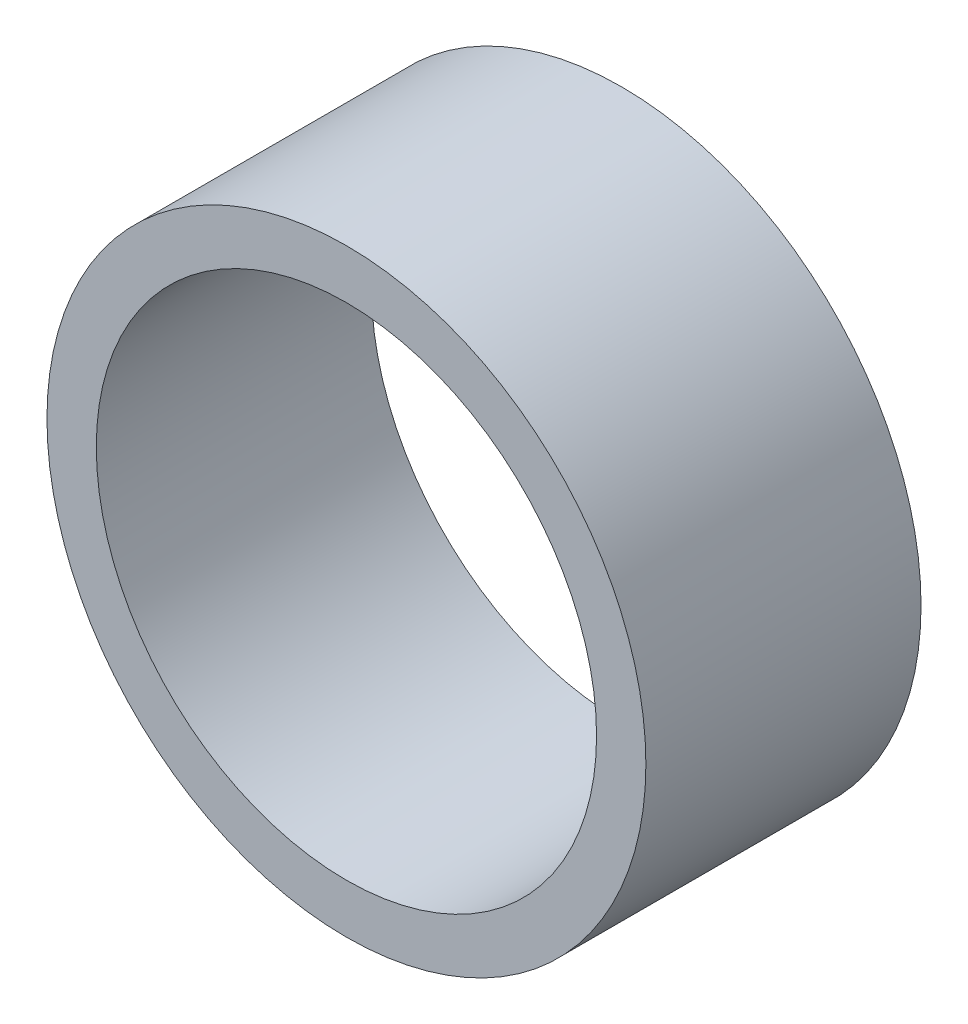
SolidWorks part; units mm, degrees
ref_plane "Plan de face" through (0, 0, 0) normal (0, 0, 1) x (1, 0, 0)
ref_plane "Plan de dessus" through (0, 0, 0) normal (0, 1, 0) x (1, 0, 0)
ref_plane "Plan de droite" through (0, 0, 0) normal (1, 0, 0) x (0, 0, -1)
sketch "Esquisse1" plane through (0, 0, 0) normal (0, 0, 1) x (1, 0, 0)
  circle A0 centre (0, 0) radius 10.775
  circle A1 centre (0, 0) radius 9
  dimension "D1" = 18
  dimension "D2" = 21.55
extrude "Extrusion1" add sketch "Esquisse1" along normal blind 9.9
